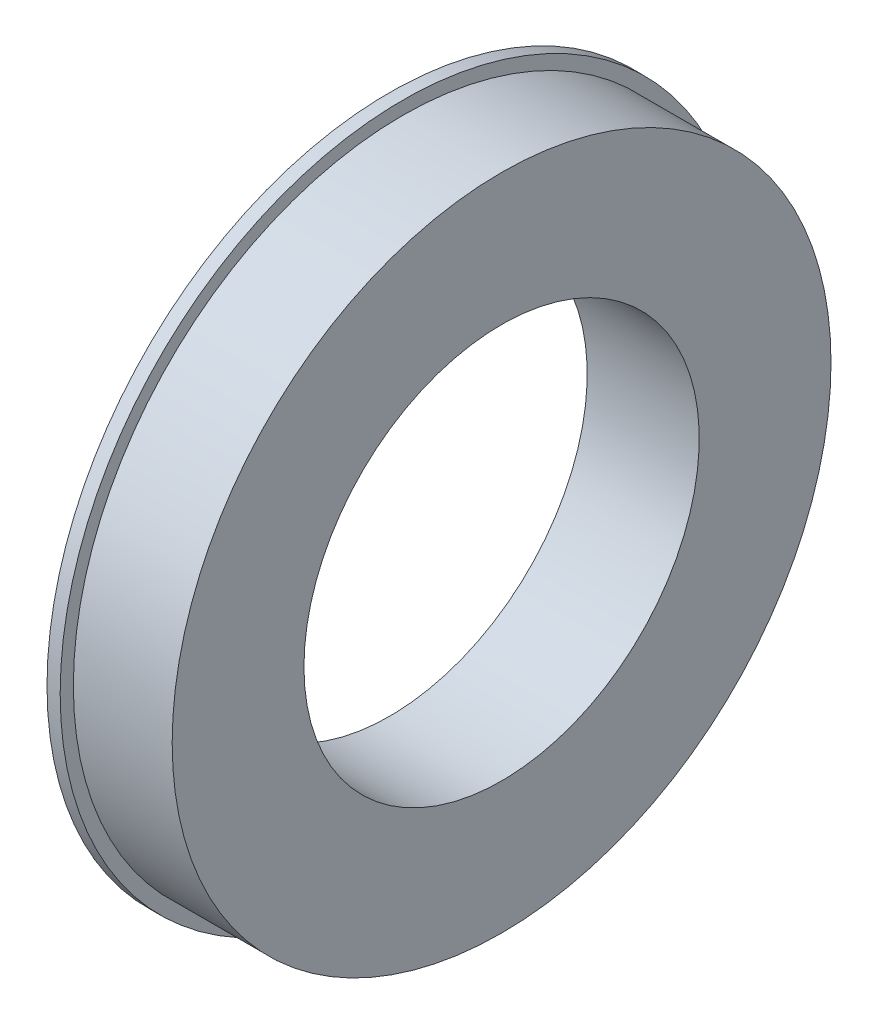
SolidWorks part; units mm, degrees
ref_plane "Front Plane" through (0, 0, 0) normal (1, 0, 0) x (0, 1, 0)
ref_plane "Top Plane" through (0, 0, 0) normal (0, 0, 1) x (0, 1, 0)
ref_plane "Right Plane" through (0, 0, 0) normal (0, 1, 0) x (-1, 0, 0)
sketch "Sketch1" plane through (0, 0, 0) normal (1, 0, 0) x (0, 1, 0)
  circle A0 centre (0, 0) radius 63.5
  circle A1 centre (0, 0) radius 38.1
  dimension "D1" = 127
  dimension "D2" = 76.2
extrude "Boss-Extrude1" add sketch "Sketch1" along normal blind 19.05
sketch "Sketch2" plane through (0, 0, 0) normal (-1, 0, 0) x (0, -1, 0)
  circle A1 centre (0, 0) radius 38.1 construction
  circle A2 centre (0, 0) radius 66.04
  circle A3 centre (0, 0) radius 66.04
  circle A4 centre (0, 0) radius 38.1
  dimension "D1" = 2.54
extrude "Boss-Extrude2" add sketch "Sketch2" along normal blind 2.54
